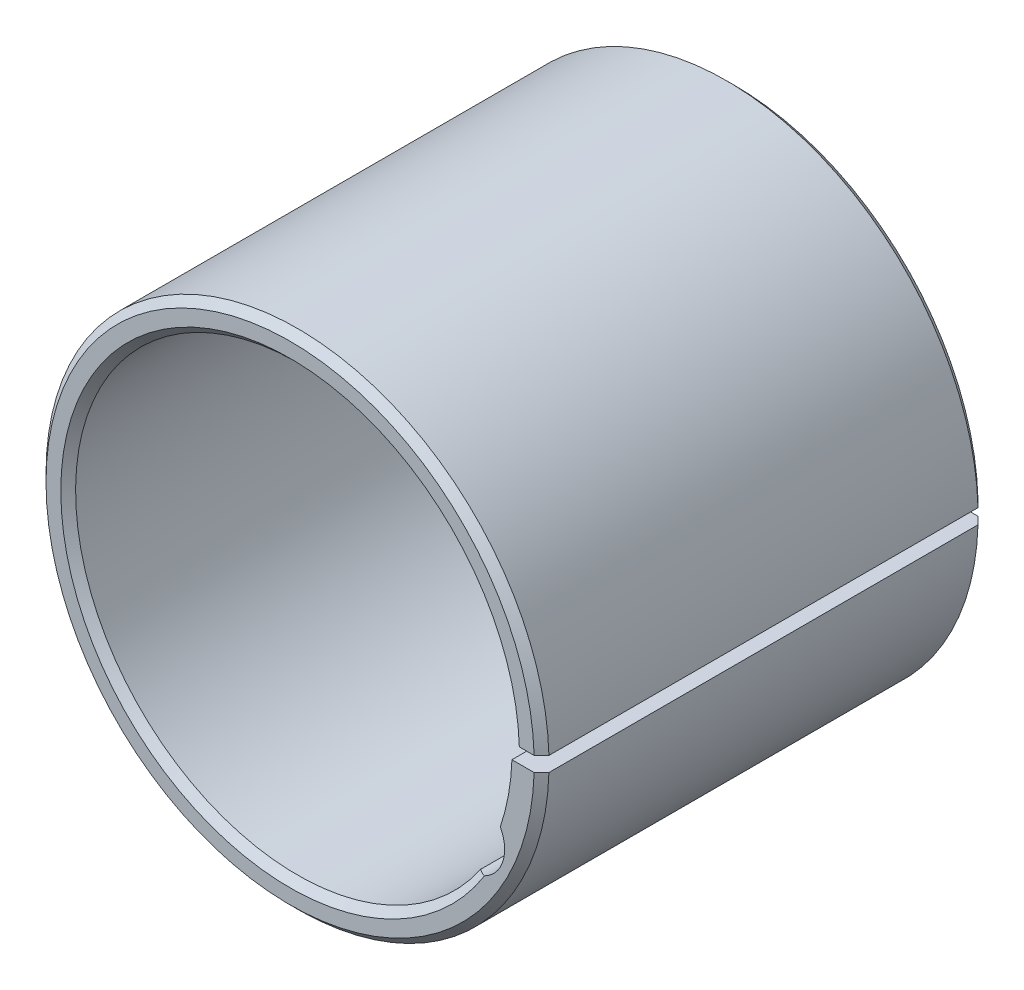
SolidWorks part; units mm, degrees
ref_plane "Plan1" through (0, 0, 0) normal (0, 0, 1) x (1, 0, 0)
ref_plane "Plan2" through (0, 0, 0) normal (0, 1, 0) x (1, 0, 0)
ref_plane "Plan3" through (0, 0, 0) normal (1, 0, 0) x (0, 0, -1)
sketch "Esquisse1" plane through (0, 0, 0) normal (0, 0, 1) x (1, 0, 0)
  line L0 (14.9917, 0.5) -> (16.9926, 0.5)
  line L1 (14.9917, -0.5) -> (16.9926, -0.5)
  arc A0 (14.9917, 0.5) -> (12.379, -8.4711) centre (0, 0) ccw
  arc A1 (16.9926, 0.5) -> (16.9926, -0.5) centre (0, 0) ccw
  arc A2 (12.379, -8.4711) -> (14.2043, -4.8206) centre (12, -6) ccw
  arc A3 (14.2043, -4.8206) -> (14.9917, -0.5) centre (0, 0) ccw
  dimension "D1" = 30
  dimension "D2" = 34
  dimension "D5" = 5
  dimension "D3" = 0.5
  dimension "D4" = 1
extrude "Base-Extrusion" add sketch "Esquisse1" along normal blind 30
chamfer "Chanfrein1" distance 0.5 angle 45 4 edges at (-14.4017, 4.1942, 30) (-17, 0, 30) (-17, 0, 0) (-14.4017, 4.1942, 0)
